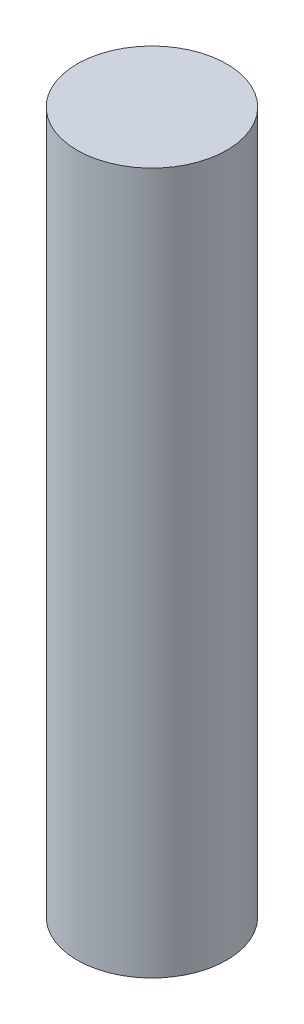
SolidWorks part; units mm, degrees
ref_plane "Plano frontal" through (0, 0, 0) normal (0, 0, 1) x (1, 0, 0)
ref_plane "Plano superior" through (0, 0, 0) normal (0, 1, 0) x (1, 0, 0)
ref_plane "Plano direito" through (0, 0, 0) normal (1, 0, 0) x (0, 0, -1)
sketch "Esboço1" plane through (0, 0, 0) normal (0, 1, 0) x (1, 0, 0)
  circle A0 centre (0, 0) radius 1.6
  dimension "D1" = 3.2
extrude "Ressalto-extrusão1" add sketch "Esboço1" along normal blind 15
